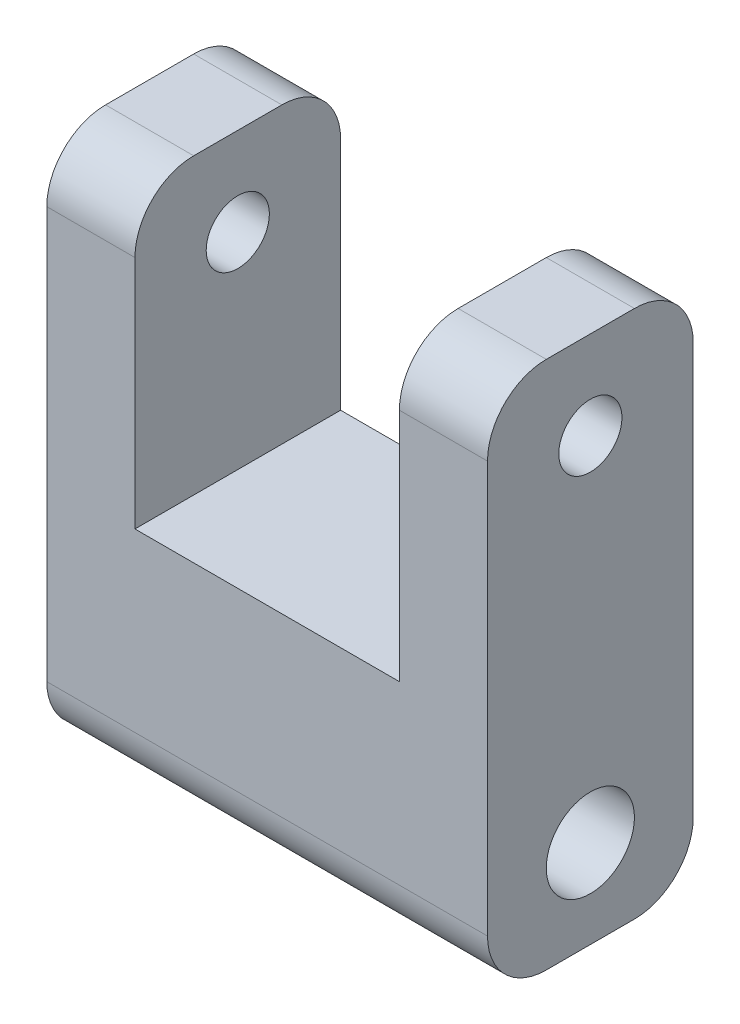
SolidWorks part; units mm, degrees
ref_plane "前视基准面" through (0, 0, 0) normal (0, 0, 1) x (1, 0, 0)
ref_plane "上视基准面" through (0, 0, 0) normal (0, 1, 0) x (1, 0, 0)
ref_plane "右视基准面" through (0, 0, 0) normal (1, 0, 0) x (0, 0, -1)
sketch "草图1" plane through (0, 0, 0) normal (0, 0, 1) x (1, 0, 0)
  line L0 (0, 0) -> (0, 18)
  line L1 (0, 18) -> (20, 18)
  line L2 (20, 18) -> (20, 0)
  line L3 (20, 0) -> (0, 0)
  dimension "D1" = 20
  dimension "D2" = 18
extrude "凸台-拉伸1" add sketch "草图1" along normal blind 15
sketch "草图2" plane through (20, 0, 0) normal (1, 0, 0) x (0, 0, -1)
  circle A0 centre (-7.5, 3) radius 1.5
  circle A1 centre (-7.5, 22) radius 1.5
  dimension "D1" = 3
  dimension "D2" = 3
  dimension "D3" = 7.5
  dimension "D4" = 3
  dimension "D5" = 7.5
  dimension "D6" = 22
extrude "切除-拉伸1" cut sketch "草图2" against normal through all
sketch "草图3" plane through (0, 0, 15) normal (0, 0, 1) x (1, 0, 0)
  line L0 (5, 18) -> (5, 8)
  line L1 (20, 18) -> (0, 18) construction
  line L2 (5, 8) -> (15, 8)
  line L3 (15, 8) -> (15, 18)
  line L4 (15, 18) -> (5, 18)
  line L5 (0, 18) -> (0, 0) construction
  dimension "D1" = 10
  dimension "D2" = 5
  dimension "D3" = 10
extrude "切除-拉伸2" cut sketch "草图3" against normal blind 15
sketch "草图5" plane through (20, 0, 0) normal (1, 0, 0) x (0, 0, -1)
  line L0 (-15, 18) -> (-15, 0)
  line L1 (-15, 0) -> (-11, 0)
  line L2 (-11, 0) -> (-11, 18)
  line L3 (-15, 18) -> (0, 18) construction
  line L4 (-11, 18) -> (-15, 18)
  line L5 (0, 18) -> (0, 0)
  line L6 (0, 0) -> (-4, 0)
  line L7 (-15, 0) -> (0, 0) construction
  line L8 (-4, 0) -> (-4, 18)
  line L9 (-4, 18) -> (0, 18)
  dimension "D1" = 4
  dimension "D2" = 4
extrude "切除-拉伸3" cut sketch "草图5" against normal through all
sketch "草图6" plane through (20, 0, 0) normal (1, 0, 0) x (0, 0, -1)
  circle A0 centre (-7.5, 15) radius 1
  dimension "D1" = 2
  dimension "D2" = 3.5
  dimension "D3" = 3
extrude "切除-拉伸4" cut sketch "草图6" against normal through all
sketch "草图8" plane through (0, 0, 11) normal (0, 0, 1) x (1, 0, 0)
  line L0 (4.3, 18) -> (4.3, 8)
  line L2 (0, 18) -> (5, 18) construction
  line L3 (4.3, 8) -> (15.7, 8)
  line L4 (15.7, 8) -> (15.7, 18)
  line L5 (15, 18) -> (20, 18) construction
  line L6 (15.7, 18) -> (4.3, 18)
  dimension "D1" = 11.4
  dimension "D2" = 0.7
extrude "切除-拉伸5" cut sketch "草图8" against normal blind 10
sketch "草图9" plane through (0, 0, 11) normal (0, 0, 1) x (1, 0, 0)
  line L0 (4.3, 18) -> (4.3, 8)
  line L1 (4.3, 8) -> (15.7, 8)
  line L2 (15.7, 8) -> (15.7, 18)
  line L3 (15.7, 18) -> (4.3, 18)
extrude "凸台-拉伸2" add sketch "草图9" against normal blind 7
sketch "草图10" plane through (20, 0, 0) normal (1, 0, 0) x (0, 0, -1)
  circle A0 centre (-7.5, 15) radius 1.075
  dimension "D1" = 2.15
extrude "切除-拉伸6" cut sketch "草图10" against normal blind 20
sketch "草图11" plane through (0, 0, 11) normal (0, 0, 1) x (1, 0, 0)
  line L0 (20, 18) -> (15, 18)
  line L1 (0, 18) -> (20, 18) construction
  line L2 (15, 18) -> (15, 0)
  line L3 (0, 0) -> (20, 0) construction
  line L4 (15, 0) -> (20, 0)
  line L5 (20, 0) -> (20, 18)
  dimension "D1" = 5
extrude "切除-拉伸7" cut sketch "草图11" against normal blind 20
sketch "草图12" plane through (0, 0, 11) normal (0, 0, 1) x (1, 0, 0)
  line L0 (3, 18) -> (3, 8)
  line L1 (0, 18) -> (15, 18) construction
  line L2 (3, 8) -> (12, 8)
  line L3 (12, 8) -> (12, 18)
  line L4 (12, 18) -> (3, 18)
  dimension "D1" = 10
  dimension "D2" = 9
  dimension "D3" = 3
extrude "切除-拉伸8" cut sketch "草图12" against normal blind 20
fillet "圆角1" radius 2 1 edges at (7.5, 0, 11)
fillet "圆角2" radius 2 1 edges at (7.5, 0, 4)
fillet "圆角3" radius 2 1 edges at (1.5, 18, 11)
fillet "圆角4" radius 2 1 edges at (13.5, 18, 11)
fillet "圆角5" radius 2 1 edges at (13.5, 18, 4)
fillet "圆角6" radius 2 1 edges at (1.5, 18, 4)
